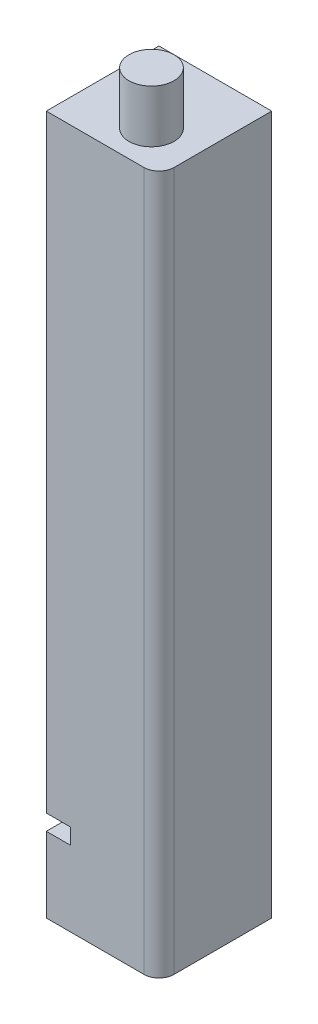
SolidWorks part; units mm, degrees
ref_plane "Front Plane" through (0, 0, 0) normal (0, 0, 1) x (1, 0, 0)
ref_plane "Top Plane" through (0, 0, 0) normal (0, 1, 0) x (1, 0, 0)
ref_plane "Right Plane" through (0, 0, 0) normal (1, 0, 0) x (0, 0, -1)
sketch "Sketch1" plane through (0, 0, 0) normal (0, 1, 0) x (1, 0, 0)
  line L0 (-68.486, 0) -> (57.6746, 0) construction
  line L1 (0, 62.7099) -> (0, -58.019) construction
  line L3 (-7.5, -7.5) -> (7.5, -7.5)
  line L4 (-7.5, -7.5) -> (-7.5, 7.5)
  line L5 (-7.5, 7.5) -> (7.5, 7.5)
  line L6 (7.5, -7.5) -> (7.5, 7.5)
  line L7 (-7.5, -7.5) -> (7.5, 7.5) construction
  line L8 (-7.5, 7.5) -> (7.5, -7.5) construction
  point P5 (0, 0)
  dimension "D1" = 15
  dimension "D2" = 15
extrude "Boss-Extrude1" add sketch "Sketch1" along normal blind 93
sketch "Sketch2" plane through (0, 93, 0) normal (0, 1, 0) x (1, 0, 0)
  line L0 (7.5, -7.5) -> (7.5, 7.5) construction
  line L1 (-7.5, -7.5) -> (7.5, -7.5) construction
  circle A0 centre (1.5, -2.5) radius 3
  dimension "D1" = 6
  dimension "D2" = 6
  dimension "D3" = 5
extrude "Boss-Extrude2" add sketch "Sketch2" along normal blind 7
sketch "Sketch3" plane through (0, 0, 7.5) normal (0, 0, 1) x (1, 0, 0)
  line L0 (-7.5, 12.1) -> (-4.3, 12.1)
  line L1 (-7.5, 93) -> (-7.5, 0) construction
  line L2 (-4.3, 12.1) -> (-4.3, 10)
  line L3 (-4.3, 10) -> (-7.5, 10)
  line L4 (-7.5, 10) -> (-7.5, 12.1)
  dimension "D1" = 10
  dimension "D2" = 2.1
  dimension "D3" = 3.2
extrude "Cut-Extrude1" cut sketch "Sketch3" against normal through all
fillet "Fillet1" radius 2 1 edges at (7.5, 46.5, 7.5)
